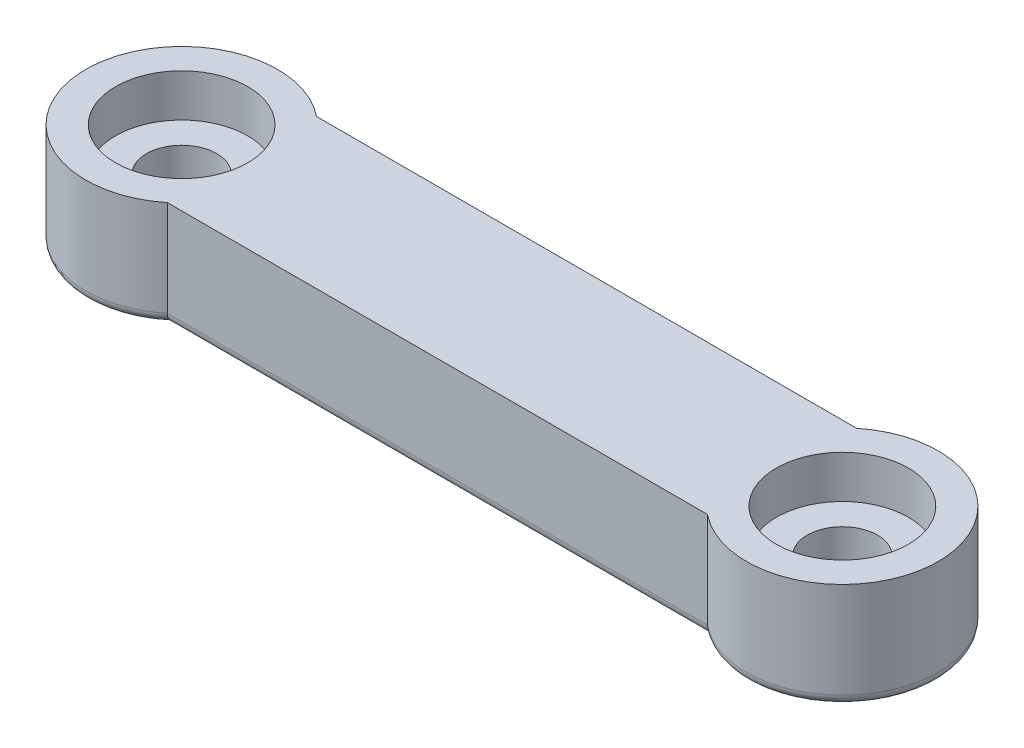
SolidWorks part; units mm, degrees
ref_plane "Front Plane" through (0, 0, 0) normal (0, 0, 1) x (1, 0, 0)
ref_plane "Top Plane" through (0, 0, 0) normal (0, 1, 0) x (1, 0, 0)
ref_plane "Right Plane" through (0, 0, 0) normal (1, 0, 0) x (0, 0, -1)
sketch "Sketch1" plane through (0, 0, 0) normal (0, 1, 0) x (1, 0, 0)
  line L1 (0, 0) -> (31, 0)
  line L2 (0, 0) -> (0, 7)
  line L3 (0, 7) -> (31, 7)
  line L4 (31, 0) -> (31, 7)
  dimension "D1" = 31
  dimension "D2" = 7
extrude "Boss-Extrude1" add sketch "Sketch1" along normal blind 5
sketch "Sketch2" plane through (0, 5, 0) normal (0, 1, 0) x (1, 0, 0)
  line L0 (31, 0) -> (31, 7) construction
  line L1 (0, 7) -> (0, 0) construction
  circle A0 centre (31, 3.5) radius 4.5
  circle A1 centre (0, 3.5) radius 4.5
  dimension "D1" = 9
  dimension "D2" = 9
extrude "Boss-Extrude2" add sketch "Sketch2" against normal blind 5
sketch "Sketch3" plane through (0, 5, 0) normal (0, 1, 0) x (1, 0, 0)
  circle A0 centre (0, 3.5) radius 1.65
  circle A1 centre (31, 3.5) radius 1.65
  dimension "D1" = 3.3
  dimension "D2" = 3.3
extrude "Cut-Extrude1" cut sketch "Sketch3" against normal through all
sketch "Sketch4" plane through (0, 5, 0) normal (0, 1, 0) x (1, 0, 0)
  circle A0 centre (0, 3.5) radius 3.1
  circle A1 centre (31, 3.5) radius 3.1
  dimension "D1" = 6.2
  dimension "D2" = 6.2
extrude "Cut-Extrude2" cut sketch "Sketch4" against normal blind 2
fillet "Fillet1" radius 0.5 4 edges at (35.5, 0, -3.5) (15.5, 0, -7) (-4.5, 0, -3.5) (15.5, 0, 0)
